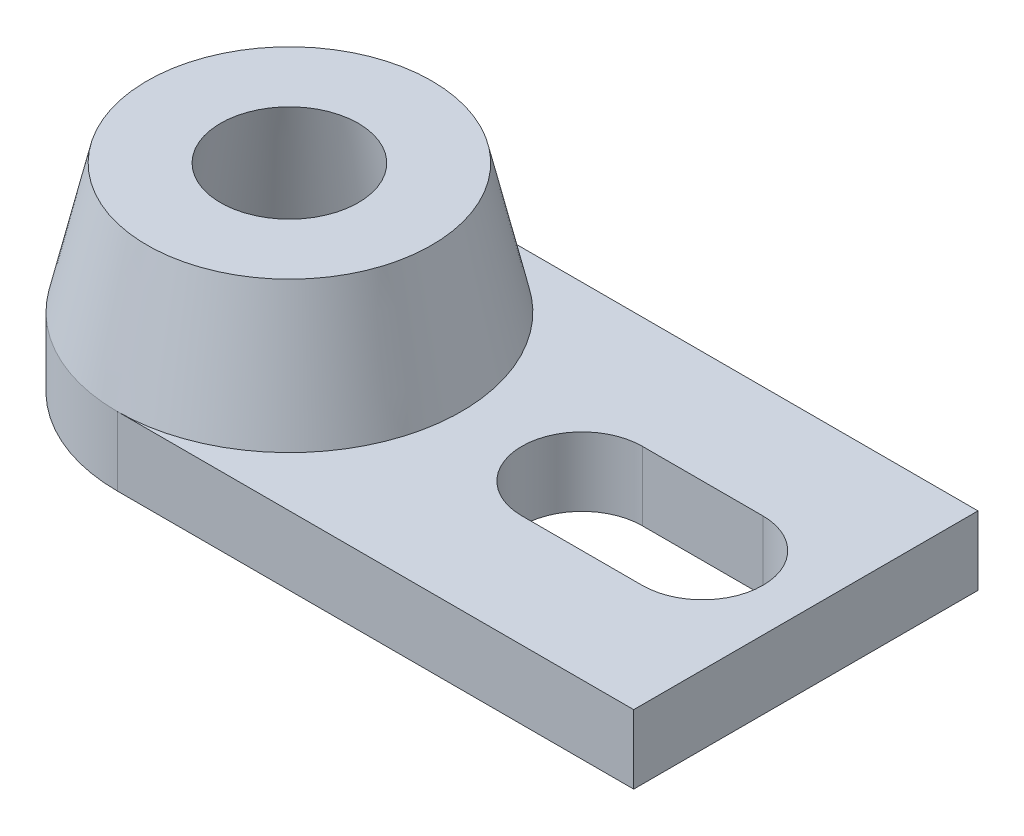
SolidWorks part; units mm, degrees
ref_plane "Alzado" through (0, 0, 0) normal (0, 0, 1) x (1, 0, 0)
ref_plane "Planta" through (0, 0, 0) normal (0, 1, 0) x (1, 0, 0)
ref_plane "Vista lateral" through (0, 0, 0) normal (1, 0, 0) x (0, 0, -1)
sketch "Croquis1" plane through (0, 0, 0) normal (0, 0, 1) x (1, 0, 0)
  line L0 (0, 0) -> (0, 56.5572) construction
  line L1 (12.0555, 0) -> (20, 0)
  line L2 (20, 0) -> (20, 8)
  line L3 (20, 8) -> (16.537, 23)
  line L4 (16.537, 23) -> (8, 23)
  line L5 (8, 23) -> (12.0555, 0)
  line L6 (20, 8) -> (20, 34.7151) construction
  line L7 (12.0555, 0) -> (12.0555, 36.6363) construction
  point P9 (0, 0)
  dimension "D1" = 20
  dimension "D2" = 15
  dimension "D3" = 13
  dimension "D4" = 10
  dimension "D5" = 8
  dimension "D6" = 8
revolve "Revolución3" add sketch "Croquis1" angle 360 about L0
ref_plane "Plano1" through (0, 0, 0) normal (0, -1, 0) x (-1, 0, 0)
sketch "Croquis2" plane through (0, 0, 0) normal (0, -1, 0) x (-1, 0, 0)
  line L0 (0, 20) -> (-60, 20)
  line L1 (-60, 20) -> (-60, -20)
  line L2 (-60, -20) -> (0, -20)
  line L3 (0, 0) -> (20, 0) construction
  line L4 (-34, 7) -> (-48, 7)
  line L5 (-34, -7) -> (-48, -7)
  circle A0 centre (0, 0) radius 20 construction
  circle A1 centre (0, 0) radius 20 construction
  arc A2 (-34, -7) -> (-34, 7) centre (-34, 0) ccw
  arc A3 (-48, 7) -> (-48, -7) centre (-48, 0) ccw
  arc A4 (0, 20) -> (0, -20) centre (0, 0) ccw
  dimension "D2" = 7
  dimension "D4" = 7
  dimension "D1" = 80
  dimension "D3" = 40
  dimension "D5" = 12
  dimension "D6" = 14
extrude "Saliente-Extruir1" add sketch "Croquis2" against normal blind 8
